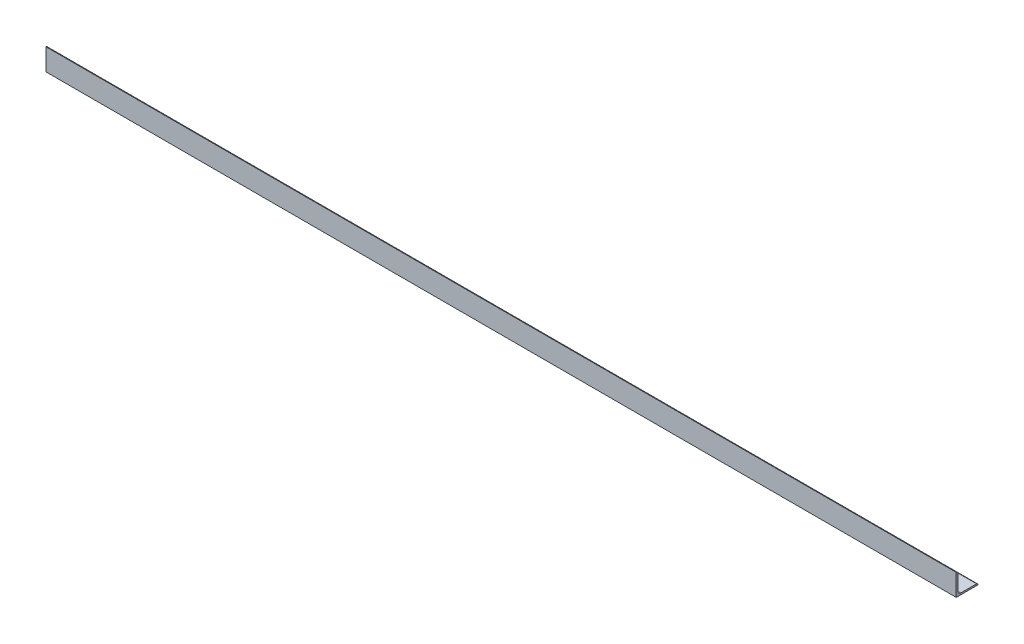
SolidWorks part; units mm, degrees
ref_plane "Front Plane" through (0, 0, 0) normal (0, 0, 1) x (1, 0, 0)
ref_plane "Top Plane" through (0, 0, 0) normal (0, 1, 0) x (1, 0, 0)
ref_plane "Right Plane" through (0, 0, 0) normal (1, 0, 0) x (0, 0, -1)
sketch "Sketch1" plane through (0, 0, 0) normal (0, 1, 0) x (1, 0, 0)
  line L0 (0, 0) -> (1674, 0)
  dimension "D1" = 1674
other "L angle (equal) 40X40X3(8)"
ref_plane "Plane1" through (0, 0, 0) normal (1, 0, 0) x (0, 0, -1)
sketch "Sketch13" plane through (0, 0, 0) normal (1, 0, 0) x (0, 0, -1)
  line L0 (0, 40) -> (0, 0)
  line L2 (3, 37) -> (3, 9)
  line L3 (9, 3) -> (37, 3)
  line L5 (40, 0) -> (0, 0)
  arc A0 (3, 37) -> (0, 40) centre (0, 37) ccw
  arc A1 (40, 0) -> (37, 3) centre (37, 0) ccw
  arc A2 (9, 3) -> (3, 9) centre (9, 9) cw
  point P8 (0, 20)
  point P9 (20, 0)
  point P10 (0, 0)
  dimension "Radius_2" = 3
  dimension "Radius_1" = 6
  dimension "V_leg" = 40
  dimension "H_leg" = 40
  dimension "thickness" = 3
